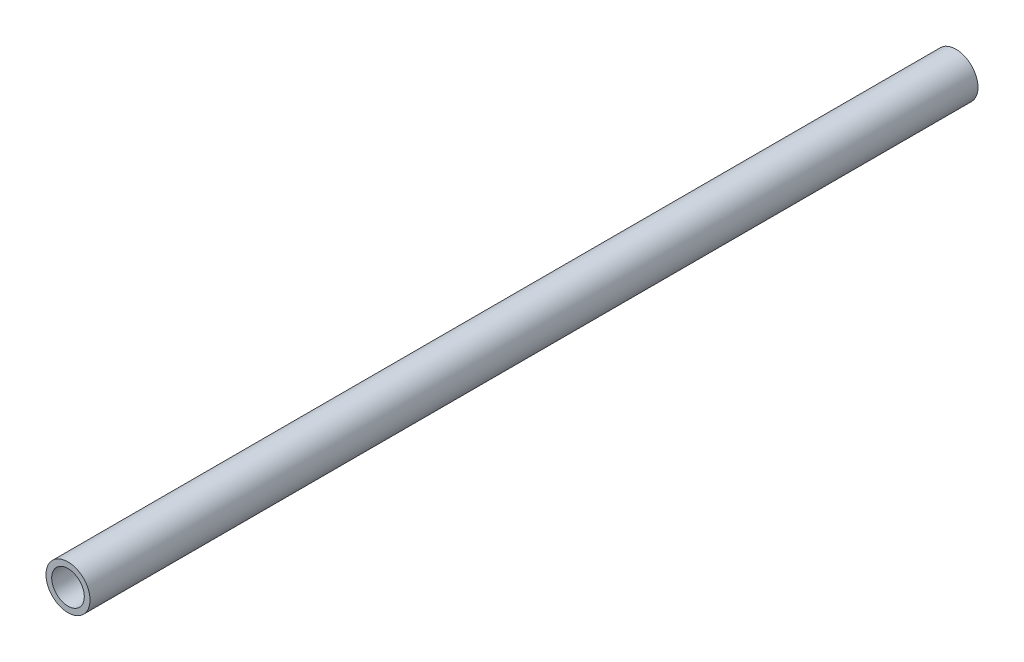
SolidWorks part; units mm, degrees
ref_plane "Front Plane" through (0, 0, 0) normal (0, 0, 1) x (1, 0, 0)
ref_plane "Top Plane" through (0, 0, 0) normal (0, 1, 0) x (1, 0, 0)
ref_plane "Right Plane" through (0, 0, 0) normal (1, 0, 0) x (0, 0, -1)
sketch "Sketch1" plane through (0, 0, 0) normal (0, 0, 1) x (1, 0, 0)
  circle A0 centre (0, 0) radius 10.668
  dimension "Pipe OD" = 21.336
extrude "Extrude-Thin1" add sketch "Sketch1" along normal mid plane 430 thin thin type one direction reverse wall 2.7686
